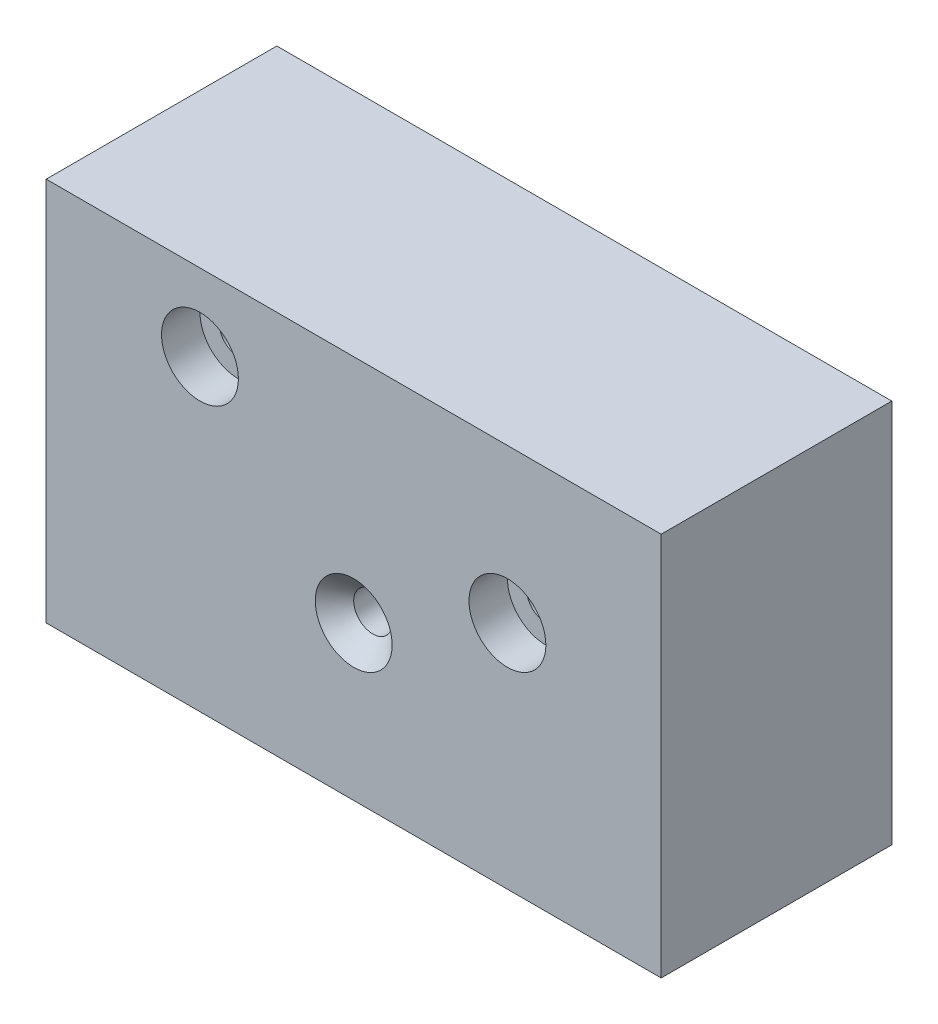
SolidWorks part; units mm, degrees
ref_plane "Front Plane" through (0, 0, 0) normal (0, 0, 1) x (1, 0, 0)
ref_plane "Top Plane" through (0, 0, 0) normal (0, 1, 0) x (1, 0, 0)
ref_plane "Right Plane" through (0, 0, 0) normal (1, 0, 0) x (0, 0, -1)
sketch "Sketch1" plane through (0, 0, 0) normal (0, 0, 1) x (1, 0, 0)
  line L1 (-49.3939, 22.2727) -> (30.6061, 22.2727)
  line L2 (-49.3939, 22.2727) -> (-49.3939, -27.7273)
  line L3 (-49.3939, -27.7273) -> (30.6061, -27.7273)
  line L4 (30.6061, 22.2727) -> (30.6061, -27.7273)
  dimension "D1" = 80
  dimension "D2" = 50
extrude "Boss-Extrude1" add sketch "Sketch1" along normal blind 30
hole_wizard "CBORE for M10 Hex Head Bolt8" positions "Sketch7" profile "Sketch8" counterbore size "M10" standard "ANSI Metric" end condition through all
sketch "Sketch7" plane through (0, 0, 30) normal (0, 0, 1) x (1, 0, 0)
  line L0 (30.6061, 22.2727) -> (-49.3939, 22.2727) construction
  line L1 (-49.3939, 22.2727) -> (-49.3939, -27.7273) construction
  point P0 (-29.3939, 12.2727)
  dimension "D1" = 10
  dimension "D2" = 20
sketch "Sketch8" plane through (-29.3939, 12.2727, 30) normal (1, 0, 0) x (0, -1, 0)
  line L0 (0, 0) -> (0, 30)
  line L1 (0, 30) -> (2.5, 30)
  line L3 (2.5, 30) -> (2.5, 5)
  line L4 (2.5, 5) -> (5, 5)
  line L5 (5, 5) -> (5, 0)
  line L7 (5, 0) -> (0, 0)
  line L11 (0, -6.35) -> (0, 107.95) construction
  dimension "Thru Hole Dia." = 5
  dimension "Thru Hole Depth" = 30
  dimension "C'Bore Dia." = 10
  dimension "C'Bore Depth" = 5
hole_wizard "CBORE for M10 Hex Head Bolt9" positions "Sketch11" profile "Sketch12" counterbore size "M10" standard "ANSI Metric" end condition through all
sketch "Sketch11" plane through (0, 0, 30) normal (0, 0, 1) x (1, 0, 0)
  line L0 (30.6061, -27.7273) -> (30.6061, 22.2727) construction
  line L1 (-49.3939, -27.7273) -> (30.6061, -27.7273) construction
  point P0 (10.6061, 2.2727)
  dimension "D1" = 20
  dimension "D2" = 30
sketch "Sketch12" plane through (10.6061, 2.2727, 30) normal (1, 0, 0) x (0, -1, 0)
  line L0 (0, 0) -> (0, 30)
  line L1 (0, 30) -> (2.5, 30)
  line L3 (2.5, 30) -> (2.5, 5)
  line L4 (2.5, 5) -> (5, 5)
  line L5 (5, 5) -> (5, 0)
  line L7 (5, 0) -> (0, 0)
  line L11 (0, -6.35) -> (0, 107.95) construction
  dimension "Thru Hole Dia." = 5
  dimension "Thru Hole Depth" = 30
  dimension "C'Bore Dia." = 10
  dimension "C'Bore Depth" = 5
hole_wizard "CSK for M10 Flat Head Machine Screw1" positions "Sketch13" profile "Sketch14" countersink size "M10" standard "ANSI Metric" end condition through all
sketch "Sketch13" plane through (0, 0, 30) normal (0, 0, 1) x (1, 0, 0)
  line L0 (-49.3939, 22.2727) -> (-49.3939, -27.7273) construction
  line L1 (-49.3939, -27.7273) -> (30.6061, -27.7273) construction
  point P0 (-9.3939, -7.7273)
  dimension "D1" = 40
  dimension "D2" = 20
sketch "Sketch14" plane through (-9.3939, -7.7273, 30) normal (1, 0, 0) x (0, -1, 0)
  line L0 (0, 0) -> (0, 30)
  line L1 (0, 30) -> (2.5, 30)
  line L2 (2.5, 30) -> (2.5, 2.5)
  line L3 (2.5, 2.5) -> (5, 0)
  line L5 (5, 0) -> (0, 0)
  line L6 (-2.5, 2.5) -> (-5, 0) construction
  line L11 (0, -6.35) -> (0, 107.95) construction
  dimension "Thru Hole Dia." = 5
  dimension "Thru Hole Depth" = 30
  dimension "Near C'Sink Dia." = 10
  dimension "Near C'Sink Angle" = 90
